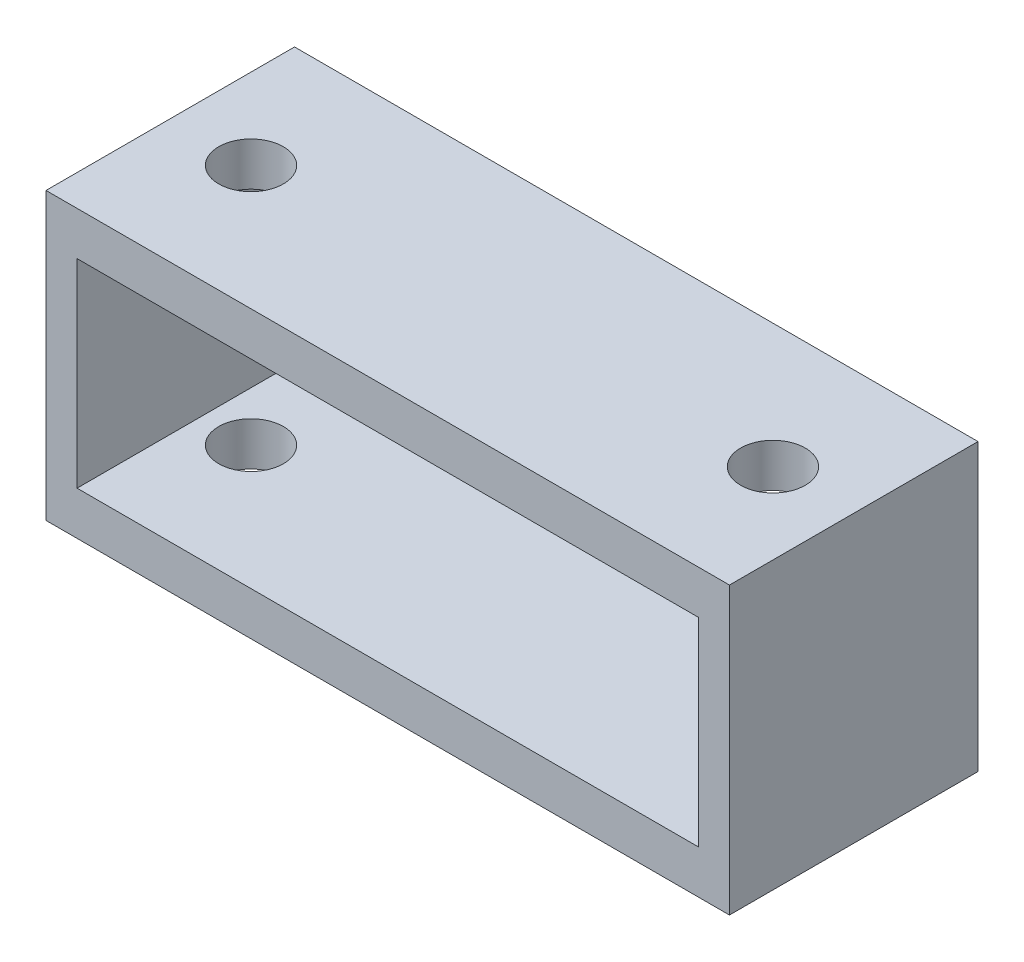
SolidWorks part; units mm, degrees
ref_plane "前视基准面" through (0, 0, 0) normal (0, 0, 1) x (1, 0, 0)
ref_plane "上视基准面" through (0, 0, 0) normal (0, 1, 0) x (1, 0, 0)
ref_plane "右视基准面" through (0, 0, 0) normal (1, 0, 0) x (0, 0, -1)
sketch "草图1" plane through (0, 0, 0) normal (0, 1, 0) x (1, 0, 0)
  line L1 (-27.5, -10) -> (27.5, -10)
  line L2 (-27.5, -10) -> (-27.5, 10)
  line L3 (-27.5, 10) -> (27.5, 10)
  line L4 (27.5, -10) -> (27.5, 10)
  line L5 (-27.5, -10) -> (27.5, 10) construction
  line L6 (-27.5, 10) -> (27.5, -10) construction
  point P0 (0, 0)
  dimension "D1" = 20
  dimension "D2" = 55
extrude "凸台-拉伸1" add sketch "草图1" along normal blind 23
sketch "草图2" plane through (0, 0, 10) normal (0, 0, 1) x (1, 0, 0)
  line L0 (-27.5, 11.5) -> (27.5, 11.5) construction
  line L1 (-27.5, 23) -> (-27.5, 0) construction
  line L2 (27.5, 23) -> (27.5, 0) construction
  line L3 (0, 0) -> (0, 23) construction
  line L4 (-27.5, 23) -> (27.5, 23) construction
  line L6 (-25, 3.5) -> (25, 3.5)
  line L7 (-25, 3.5) -> (-25, 19.5)
  line L8 (-25, 19.5) -> (25, 19.5)
  line L9 (25, 3.5) -> (25, 19.5)
  line L10 (-25, 3.5) -> (25, 19.5) construction
  line L11 (-25, 19.5) -> (25, 3.5) construction
  point P11 (0, 11.5)
  dimension "D1" = 50
  dimension "D2" = 16
extrude "切除-拉伸1" cut sketch "草图2" against normal up to next
sketch "草图3" plane through (0, 23, 0) normal (0, 1, 0) x (1, 0, 0)
  line L0 (-27.5, 0) -> (27.5, 0) construction
  line L1 (-27.5, 10) -> (-27.5, -10) construction
  line L2 (27.5, -10) -> (27.5, 10) construction
  circle A0 centre (-21, 0) radius 2.6
  circle A1 centre (21, 0) radius 2.6
  dimension "D3" = 5.2
  dimension "D4" = 5.2
  dimension "D1" = 6.5
  dimension "D2" = 6.5
extrude "切除-拉伸2" cut sketch "草图3" against normal up to surface (23 mm away) up to face at (0, 0, 0)
